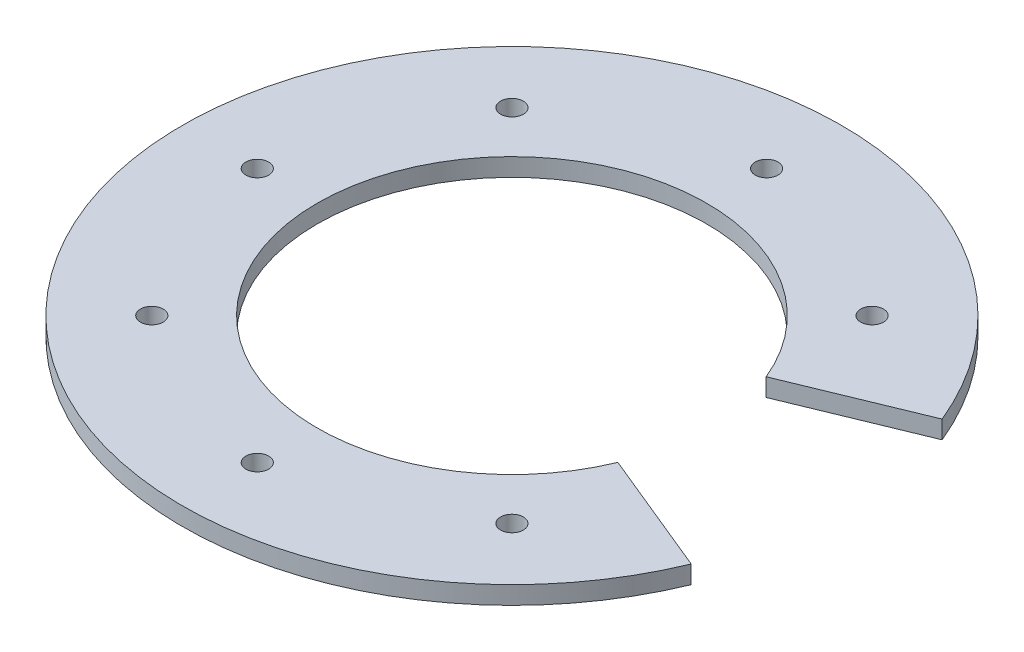
SolidWorks part; units mm, degrees
ref_plane "Front Plane" through (0, 0, 0) normal (0, 0, 1) x (1, 0, 0)
ref_plane "Top Plane" through (0, 0, 0) normal (0, 1, 0) x (1, 0, 0)
ref_plane "Right Plane" through (0, 0, 0) normal (1, 0, 0) x (0, 0, -1)
sketch "Sketch1" plane through (0, 0, 0) normal (0, 1, 0) x (1, 0, 0)
  line L0 (30.052, 12.3744) -> (50.8573, 20.9412)
  line L1 (0, 0) -> (40.6, 0) construction
  line L2 (30.052, -12.3744) -> (50.8573, -20.9412)
  arc A0 (50.8573, 20.9412) -> (50.8573, -20.9412) centre (0, 0) ccw
  arc A1 (30.052, 12.3744) -> (30.052, -12.3744) centre (0, 0) ccw
  arc A10 (39.2988, 16.1819) -> (39.2988, -16.1819) centre (0, 0) ccw construction
  circle A11 centre (0, 42.5) radius 1.9
  circle A12 centre (30.052, 30.052) radius 1.9
  circle A14 centre (30.052, -30.052) radius 1.9
  circle A15 centre (0, -42.5) radius 1.9
  circle A16 centre (-30.052, -30.052) radius 1.9
  circle A17 centre (-42.5, 0) radius 1.9
  circle A18 centre (-30.052, 30.052) radius 1.9
  arc A20 (40.6, 0) -> (42.4575, -1.8995) centre (42.5, 0) ccw [skipped]
  point P23 (0, 0)
  point P24 (0, 0)
  dimension "D1" = 110
  dimension "D2" = 65
  dimension "D3" = 3.8
  dimension "D4" = 85
  dimension "D5" = 8
extrude "Boss-Extrude1" add sketch "Sketch1" along normal blind 3
